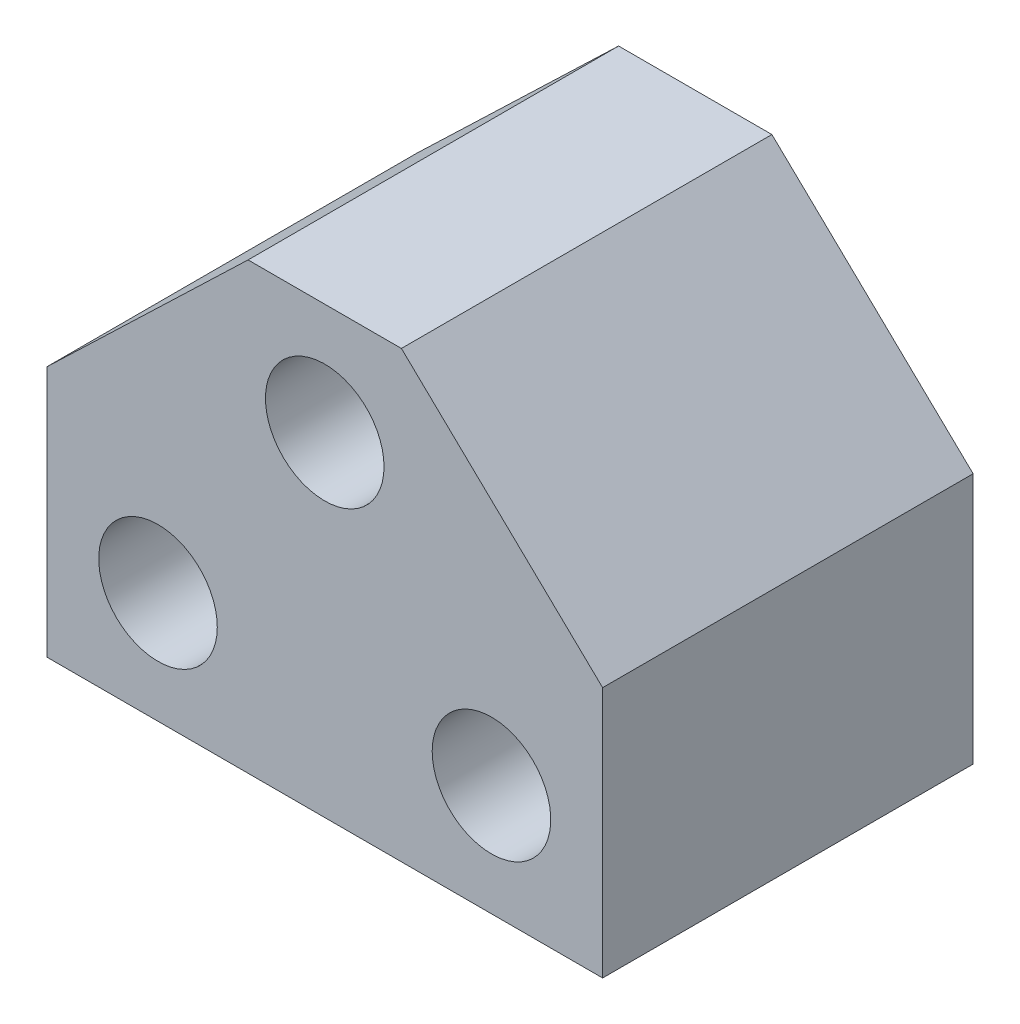
SolidWorks part; units mm, degrees
ref_plane "Front Plane" through (0, 0, 0) normal (0, 0, 1) x (1, 0, 0)
ref_plane "Top Plane" through (0, 0, 0) normal (0, 1, 0) x (1, 0, 0)
ref_plane "Right Plane" through (0, 0, 0) normal (1, 0, 0) x (0, 0, -1)
sketch "Sketch1" plane through (0, 0, 0) normal (0, 0, 1) x (1, 0, 0)
  line L2 (7.5, 0) -> (-7.5, 0)
  line L3 (0, 9) -> (0, 0) construction
  line L4 (-7.5, 0) -> (-7.5, 6)
  line L5 (7.5, 0) -> (7.5, 6)
  line L6 (-2.069, 12) -> (2.069, 12)
  line L7 (2.069, 12) -> (7.5, 6.7866)
  line L8 (7.5, 6.7866) -> (7.5, 6)
  line L9 (-2.069, 12) -> (-7.5, 6.7866)
  line L10 (-7.5, 6.7866) -> (-7.5, 6)
  circle A1 centre (0, 9) radius 1.6
  circle A2 centre (-4.5, 3) radius 1.6
  circle A3 centre (4.5, 3) radius 1.6
  point P4 (0, 0)
  point P5 (0, 0)
  point P16 (0, 12)
  dimension "D1" = 3.2
  dimension "D2" = 3
  dimension "D3" = 6.7866
  dimension "D4" = 9
  dimension "D5" = 9
  dimension "D6" = 15
  dimension "D7" = 7.5283
  dimension "D8" = 136.172
  dimension "D9" = 4.1379
extrude "Boss-Extrude1" add sketch "Sketch1" along normal blind 10
